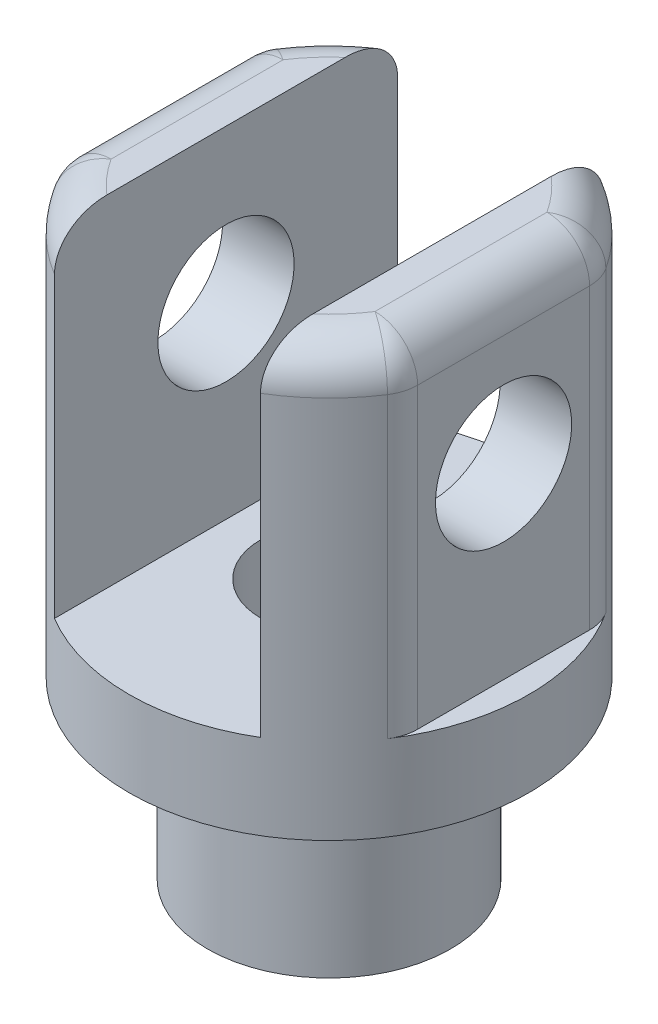
SolidWorks part; units mm, degrees
material "6061-T6 (SS)"
ref_plane "Front Plane" through (0, 0, 0) normal (0, 0, 1) x (1, 0, 0)
ref_plane "Top Plane" through (0, 0, 0) normal (0, 1, 0) x (1, 0, 0)
ref_plane "Right Plane" through (0, 0, 0) normal (1, 0, 0) x (0, 0, -1)
sketch "Sketch1" plane through (0, 0, 0) normal (0, 1, 0) x (1, 0, 0)
  circle A0 centre (0, 0) radius 7.1438
  dimension "D2" = 14.2875
extrude "Boss-Extrude1" add sketch "Sketch1" along normal blind 10.25
sketch "Sketch2" plane through (0, 10.25, 0) normal (0, 1, 0) x (1, 0, 0)
  circle A0 centre (0, 0) radius 11.75
extrude "Boss-Extrude2" add sketch "Sketch2" along normal blind 25
sketch "Sketch3" plane through (0, 35.25, 0) normal (0, 1, 0) x (1, 0, 0)
  line L0 (0, 0) -> (6.05, 0) construction
  line L5 (0, 0) -> (-6.05, 0) construction
  line L6 (-6.05, 10.0727) -> (-6.05, -10.0727)
  line L7 (6.05, 10.0727) -> (6.05, -10.0727)
  line L8 (-6.05, 0) -> (-10.25, 0) construction
  line L9 (6.05, 0) -> (10.25, 0) construction
  line L10 (-10.25, 5.7446) -> (-10.25, -5.7446)
  line L11 (10.25, 5.7446) -> (10.25, -5.7446)
  circle A1 centre (0, 0) radius 11.75
  circle M10 centre (0, 0) radius 11.75
sketch "Sketch6" plane through (0, 0, 0) normal (0, -1, 0) x (1, 0, 0)
  circle A0 centre (0, 0) radius 4
extrude "Cut-Extrude4" cut sketch "Sketch6" against normal blind 20
extrude "Cut-Extrude5" cut sketch "Sketch3" against normal blind 20 contours L7 L6 M10 | L10 M10 | L11 M10 | A1
sketch "Sketch7" plane through (-10.25, 0, 0) normal (-1, 0, 0) x (0, 0, 1)
  line L0 (0, 26.25) -> (0, 35.25) construction
  circle A0 centre (0, 26.25) radius 4
  point P4 (0, 0)
  dimension "D1" = 8
extrude "Cut-Extrude6" cut sketch "Sketch7" against normal blind 30
fillet "Fillet1" radius 2.5 4 edges at (10.25, 25.25, -5.7446) (10.25, 25.25, 5.7446) (-10.25, 25.25, -5.7446) (-10.25, 25.25, 5.7446)
fillet "Fillet2" radius 2.5 10 edges at (-8.1551, 35.25, -8.4592) (-10.1465, 35.25, -5.7616) (-8.1551, 35.25, 8.4592) (-10.1465, 35.25, 5.7616) (8.1551, 35.25, -8.4592) (10.1465, 35.25, -5.7616) (8.1551, 35.25, 8.4592) (10.1465, 35.25, 5.7616) (-10.25, 35.25, 0) (10.25, 35.25, 0)
